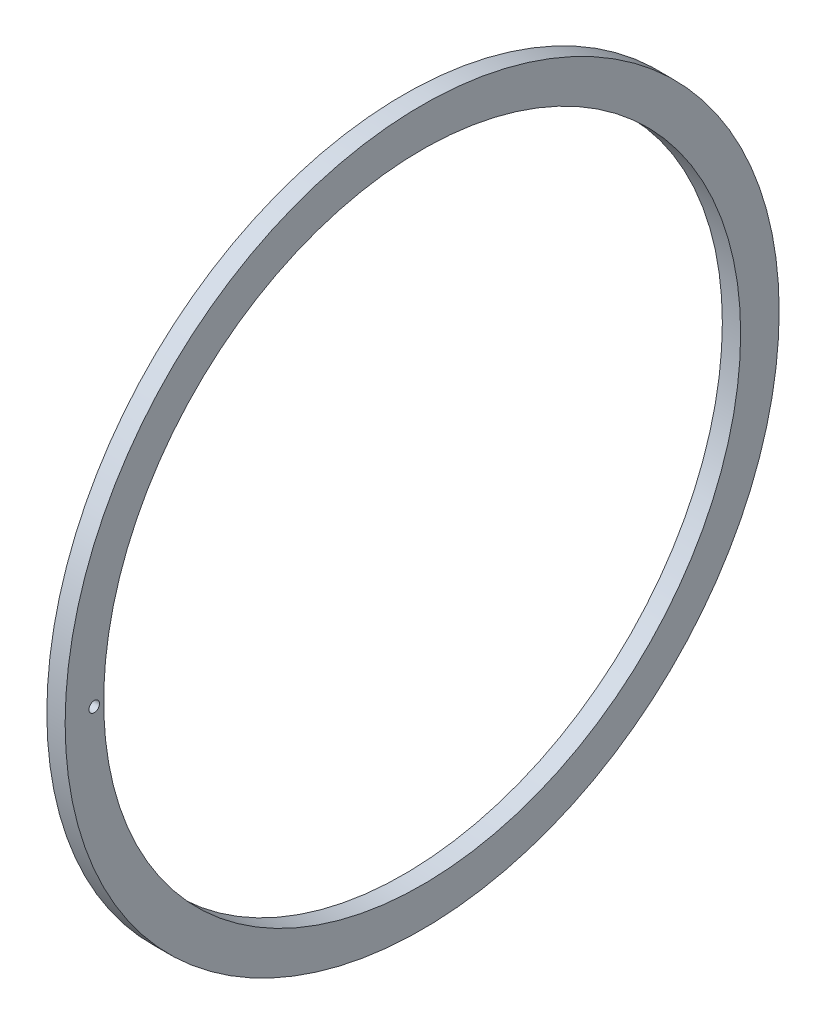
SolidWorks part; units mm, degrees
ref_plane "Front Plane" through (0, 0, 0) normal (0, 0, 1) x (1, 0, 0)
ref_plane "Top Plane" through (0, 0, 0) normal (0, 1, 0) x (1, 0, 0)
ref_plane "Right Plane" through (0, 0, 0) normal (1, 0, 0) x (0, 0, -1)
sketch "Sketch1" plane through (0, 0, 0) normal (1, 0, 0) x (0, 0, -1)
  circle A0 centre (0, 0) radius 195
  circle A2 centre (-179.1137, 0) radius 2.8993
  dimension "D1" = 390
  dimension "D3" = 5.7987
extrude "Boss-Extrude1" add sketch "Sketch1" along normal blind 10
sketch "Sketch2" plane through (10, 0, 0) normal (1, 0, 0) x (0, 0, -1)
  circle A0 centre (0, 0) radius 173.961
  dimension "D1" = 347.922
extrude "Cut-Extrude1" cut sketch "Sketch2" against normal through all both and the other way through all
